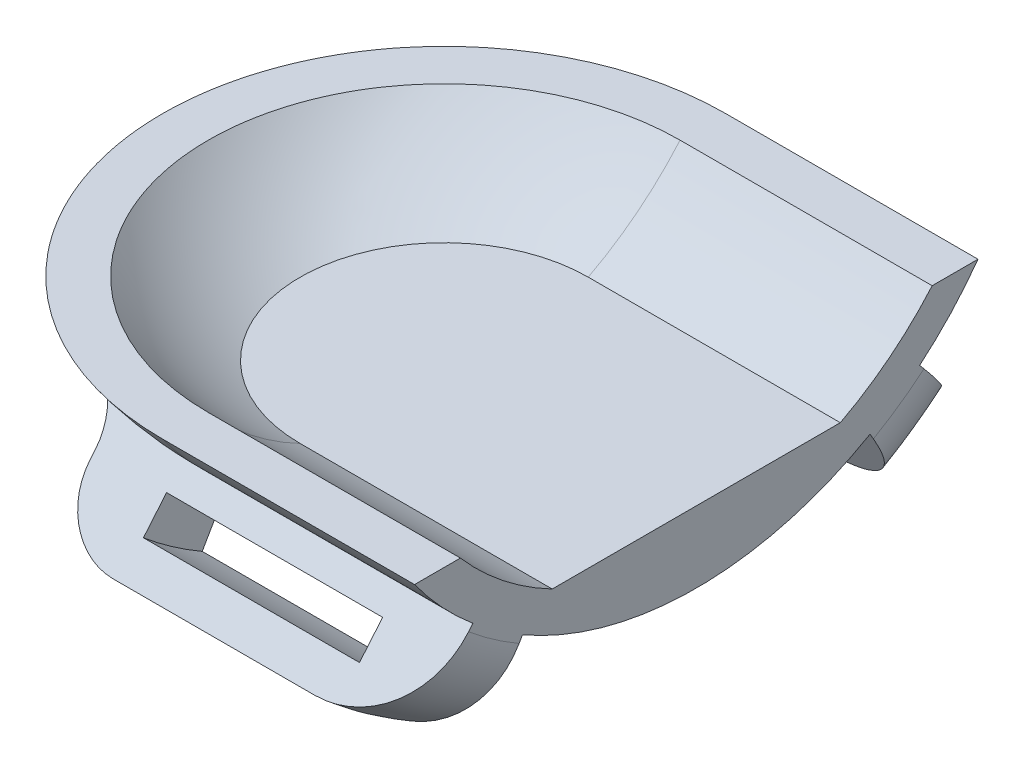
SolidWorks part; units mm, degrees
ref_plane "Front Plane" through (0, 0, 0) normal (0, 0, 1) x (1, 0, 0)
ref_plane "Top Plane" through (0, 0, 0) normal (0, 1, 0) x (1, 0, 0)
ref_plane "Right Plane" through (0, 0, 0) normal (1, 0, 0) x (0, 0, -1)
sketch "Sketch2" plane through (0, 0, 0) normal (1, 0, 0) x (0, 0, -1)
  circle A0 centre (0, 0) radius 10.9855
  circle A1 centre (0, 0) radius 12.2555
  dimension "D1" = 21.971
  dimension "D2" = 1.27
extrude "Boss-Extrude2" add sketch "Sketch2" along normal blind 15.24
sketch "Sketch3" plane through (0, 0, 0) normal (0, 1, 0) x (1, 0, 0)
  line L0 (0, 0) -> (-12.2555, 0)
  line L1 (0, 0) -> (0, 12.2555)
  circle A0 centre (0, 0) radius 12.2555
  circle A1 centre (0, 0) radius 10.9855
revolve "Revolve1" add sketch "Sketch3" angle 360 about L0
sketch "Sketch4" plane through (0, 0, 0) normal (0, 1, 0) x (1, 0, 0)
  line L0 (15.24, -12.2555) -> (15.24, 12.2555) construction
  line L1 (15.24, 12.2555) -> (8.89, 12.2555)
  line L2 (15.24, 12.2555) -> (15.24, -12.2555)
  line L3 (15.24, -12.2555) -> (8.89, -12.2555)
  line L4 (8.89, 12.2555) -> (8.89, -12.2555)
  line L5 (0, 0) -> (15.24, 0) construction
  line L6 (15.24, 12.2555) -> (0, 12.2555) construction
  line L7 (0, -12.2555) -> (15.24, -12.2555) construction
  dimension "D3" = 6.35
extrude "Cut-Extrude1" cut sketch "Sketch4" against normal through all and the other way through all
ref_plane "Plane1" through (0, 12.2555, 0) normal (0, 1, 0) x (1, 0, 0)
sketch "Sketch6" plane through (0, 12.2555, 0) normal (0, 1, 0) x (1, 0, 0)
  line L0 (8.89, 3.175) -> (-10.16, 3.175)
  line L1 (8.89, 3.175) -> (8.89, -3.175)
  line L2 (-10.16, 3.175) -> (-10.16, -3.175)
  line L3 (8.89, -3.175) -> (-10.16, -3.175)
  line L5 (8.89, -12.2555) -> (8.89, 12.2555) construction
  point P6 (8.89, 0)
  point P7 (8.89, 0)
  dimension "D1" = 6.35
  dimension "D2" = 19.05
extrude "Boss-Extrude3" add sketch "Sketch6" along normal blind 11.43 and the other way up to surface other way up to face at (0, 0, -12.2555)
sketch "Sketch7" plane through (0, 0, 3.175) normal (0, 0, 1) x (1, 0, 0)
  line L1 (-10.16, 23.6855) -> (8.89, 23.6855) construction
  line L3 (8.89, 23.6855) -> (8.89, 11.8371) construction
  circle A0 centre (4.8895, 19.685) radius 1.4605
  point P5 (4.8895, 21.1455)
  point P8 (4.8895, 18.2245)
  point P9 (6.35, 19.685)
  dimension "D1" = 2.921
  dimension "D2" = 2.54
  dimension "D3" = 2.54
extrude "Cut-Extrude3" cut sketch "Sketch7" against normal through all
sketch "Sketch10" plane through (0, 12.2555, 0) normal (0, 1, 0) x (1, 0, 0)
  line L4 (0, -3.175) -> (0, 3.175)
  line L5 (-10.16, -3.175) -> (0, -3.175)
  line L6 (-10.16, 3.175) -> (-10.16, -3.175)
  line L7 (0, 3.175) -> (-10.16, 3.175)
  line L8 (0, -3.175) -> (0, 3.175)
  line L9 (-10.16, -3.175) -> (0, -3.175)
  line L10 (-10.16, 3.175) -> (-10.16, -3.175)
  line L11 (0, 3.175) -> (-10.16, 3.175)
  dimension "D1" = 0
extrude "Boss-Extrude5" add sketch "Sketch10" against normal up to surface (0.4184 mm away)
sketch "Sketch8" plane through (8.89, 0, 0) normal (1, 0, 0) x (0, 0, -1)
  line L0 (-1.5875, 23.6855) -> (1.5875, 23.6855)
  line L1 (-1.5875, 23.6855) -> (-1.5875, 16.0655)
  line L2 (1.5875, 23.6855) -> (1.5875, 16.0655)
  line L3 (-1.5875, 16.0655) -> (1.5875, 16.0655)
  line L4 (-3.175, 23.6855) -> (3.175, 23.6855) construction
  point P6 (0, 23.6855)
  dimension "D1" = 7.62
  dimension "D2" = 3.175
pattern_linear "LPattern1" count 3 spacing 5.334 along (-1, 0, 0) of "Cut-Extrude3"
extrude "Cut-Extrude4" cut sketch "Sketch8" against normal through all
fillet "Fillet5" radius 5.08 4 edges at (-10.16, 23.6855, -2.3812) (8.89, 23.6855, -2.3813) (-10.16, 23.6855, 2.3813) (8.89, 23.6855, 2.3812)
fillet "Fillet6" radius 2.54 5 edges at (4.445, 11.8371, -3.175) (-5.8404, 10.2959, 3.175) (-10.16, 6.8536, 0) (-5.8404, 10.2959, -3.175) (4.445, 11.8371, 3.175)
sketch "Sketch11" plane through (8.89, 0, 0) normal (1, 0, 0) x (0, 0, -1)
  line L0 (-5.08, -9.7404) -> (5.08, -9.7404)
  circle A0 centre (0, 0) radius 10.9855 construction
  circle A1 centre (0, 0) radius 10.9855
  circle M1 centre (0, 0) radius 10.9855
  dimension "D1" = 10.16
extrude "Boss-Extrude6" add sketch "Sketch11" against normal up to surface (8.89 mm away) contours L0 M1
sketch "Sketch13" plane through (0, 0, 3.175) normal (0, 0, 1) x (1, 0, 0)
  line L0 (-10.16, 16.0655) -> (8.89, 16.0655) construction
  line L1 (-10.16, 16.0655) -> (8.89, 16.0655)
  line L2 (8.89, 18.6055) -> (8.89, 13.6472) construction
  line L3 (-1.27, 14.7955) -> (6.35, 14.7955)
  line L4 (-1.27, 14.7955) -> (-1.27, 12.2555)
  line L5 (-1.27, 12.2555) -> (6.35, 12.2555)
  line L6 (6.35, 14.7955) -> (6.35, 12.2555)
  line L7 (-1.27, 14.7955) -> (6.35, 12.2555) construction
  line L8 (-1.27, 12.2555) -> (6.35, 14.7955) construction
  point P2 (2.54, 13.5255)
  arc M3 (-10.16, 9.1115) -> (0, 13.6472) centre (0, 0) cw
  line M4 (0, 13.6472) -> (8.89, 13.6472)
  dimension "D1" = 7.62
  dimension "D2" = 2.54
  dimension "D3" = 1.27
  dimension "D4" = 2.54
extrude "Cut-Extrude5" cut sketch "Sketch13" against normal through all and the other way through all contours L6 L3 L4 M3 M4 | L6 L4 L5 M4 M3
sketch "Sketch14" plane through (0, 0, 3.175) normal (0, 0, 1) x (1, 0, 0)
  line L0 (8.89, -12.2555) -> (8.89, 11.3043) construction
  line L1 (8.89, -7.1755) -> (-12.2555, -7.1755)
  line L2 (8.89, -7.1755) -> (8.89, 23.6855)
  line L3 (8.89, 23.6855) -> (-12.2555, 23.6855)
  line L4 (-12.2555, -7.1755) -> (-12.2555, 23.6855)
  line L6 (-5.08, 23.6855) -> (3.81, 23.6855) construction
  line L7 (0, -12.2555) -> (8.89, -12.2555) construction
  arc A0 (-10.5197, 6.2875) -> (0, -12.2555) centre (0, 0) ccw construction
  dimension "D1" = 5.08
extrude "Cut-Extrude6" cut sketch "Sketch14" against normal through all and the other way through all
sketch "Sketch16" plane through (8.89, 0, 0) normal (1, 0, 0) x (0, 0, -1)
  line L0 (0, 0) -> (-10.1532, -12.1001)
  line L1 (0, 0) -> (-7.8977, -13.6793)
  line L2 (0, 0) -> (7.8977, -13.6793)
  line L3 (0, 0) -> (-10.1532, -12.1001)
  line L4 (8.3183, -7.1755) -> (-8.3183, -7.1755) construction
  line L5 (0, 0) -> (10.1532, -12.1001)
  circle A0 centre (0, 0) radius 15.7955
  circle A1 centre (0, 0) radius 14.7955
  arc A2 (-9.9353, -7.1755) -> (9.9353, -7.1755) centre (0, 0) ccw construction
  circle A3 centre (0, 0) radius 10.9855
  arc A4 (5.08, -9.7404) -> (8.3183, -7.1755) centre (0, 0) ccw construction
  arc M1 (-9.9353, -7.1755) -> (9.9353, -7.1755) centre (0, 0) ccw
  arc M3 (8.3183, -7.1755) -> (5.08, -9.7404) centre (0, 0) cw
  arc M5 (-5.08, -9.7404) -> (-8.3183, -7.1755) centre (0, 0) cw
  dimension "D1" = 2.54
  dimension "D2" = 1
  dimension "D3" = 10
  dimension "D4" = 50
extrude "Boss-Extrude7" add sketch "Sketch16" against normal blind 12.7 contours A1 L3 A0 L1 | L0 A1 L1 M1 | L1 L0 M5 M1 | L5 L2 M3 M1 | L2 A1 L5 M1 | A1 L2 A0 L5
sketch "Sketch17" plane through (0, 0, 0) normal (0, 0.6428, 0.766) x (1, 0, 0)
  line L0 (8.89, -12.2555) -> (8.89, -15.7955) construction
  line L1 (-1.27, -13.2555) -> (6.35, -13.2555)
  line L2 (-1.27, -13.2555) -> (-1.27, -14.5255)
  line L3 (-1.27, -14.5255) -> (6.35, -14.5255)
  line L4 (6.35, -13.2555) -> (6.35, -14.5255)
  line L5 (-1.27, -13.2555) -> (6.35, -14.5255) construction
  line L6 (-1.27, -14.5255) -> (6.35, -13.2555) construction
  line L7 (-3.81, -15.7955) -> (8.89, -15.7955) construction
  point P0 (2.54, -13.8905)
  point P5 (8.89, -14.0255)
  dimension "D1" = 2.54
  dimension "D2" = 7.62
  dimension "D3" = 1.27
  dimension "D4" = 1.27
ref_axis "Axis1" through (8.89, 0, 0) along (-1, 0, 0)
revolve "Cut-Revolve1" cut sketch "Sketch17" angle 360 about axis through (8.89, 0, 0) along (-1, 0, 0)
fillet "Fillet7" radius 2.286 4 edges at (-3.81, -9.5417, -6.6811) (-3.81, -12.9389, -9.0599) (-3.81, -9.5417, 6.6811) (-3.81, -12.9389, 9.0599)
fillet "Fillet8" radius 3.302 2 edges at (8.89, -12.9389, -9.0599) (8.89, -12.9389, 9.0599)
